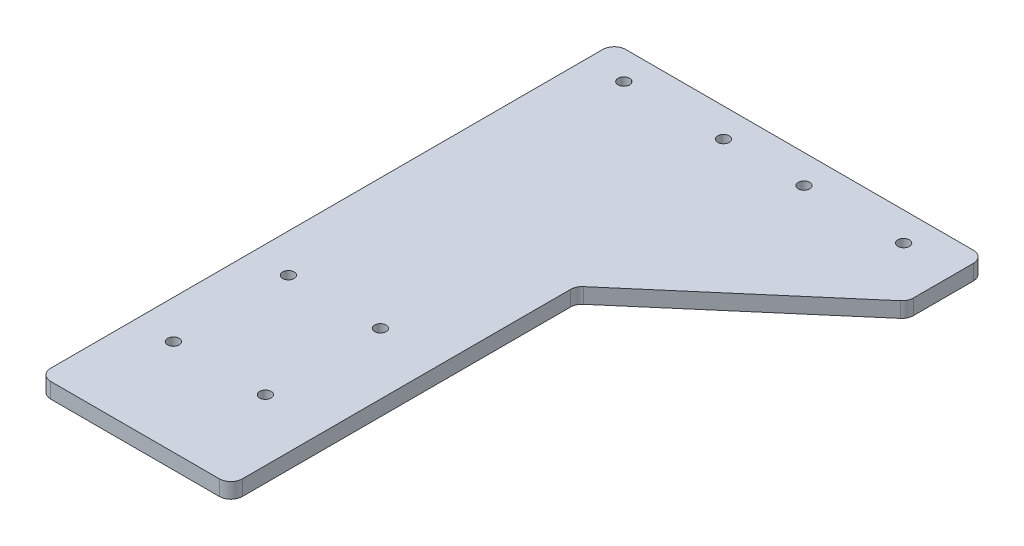
SolidWorks part; units mm, degrees
ref_plane "前视基准面" through (0, 0, 0) normal (0, 0, 1) x (1, 0, 0)
ref_plane "上视基准面" through (0, 0, 0) normal (0, 1, 0) x (1, 0, 0)
ref_plane "右视基准面" through (0, 0, 0) normal (1, 0, 0) x (0, 0, -1)
sketch "草图1" plane through (0, 0, 0) normal (0, 1, 0) x (1, 0, 0)
  line L0 (100, 150) -> (75, 0)
  line L1 (0, 0) -> (75, 0)
  line L2 (0, 0) -> (0, 150)
  line L3 (0, 150) -> (100, 150)
  dimension "D1" = 100
  dimension "D2" = 150
  dimension "D3" = 25
extrude "凸台-拉伸1" add sketch "草图1" along normal blind 4
sketch "草图2" plane through (0, 4, 0) normal (0, 1, 0) x (1, 0, 0)
  line L0 (0, 0) -> (75, 0) construction
  line L1 (0, 150) -> (0, 0) construction
  circle A0 centre (10, 25) radius 1.5
  circle A1 centre (34, 55) radius 1.5
  circle A2 centre (34, 25) radius 1.5
  circle A3 centre (10, 55) radius 1.5
  circle A4 centre (35, 25) radius 1.5 [skipped]
  circle A5 centre (35, 55) radius 1.5 [skipped]
  dimension "D1" = 25
  dimension "D2" = 10
  dimension "D3" = 2
  dimension "D4" = 2
  dimension "D5" = 2
extrude "切除-拉伸1" cut sketch "草图2" against normal blind 4
sketch "草图3" plane through (0, 4, 0) normal (0, 1, 0) x (1, 0, 0)
  line L0 (100, 150) -> (0, 150) construction
  line L1 (0, 150) -> (0, 0) construction
  circle A0 centre (10, 142.5) radius 1.5
  circle A1 centre (36, 142.5) radius 1.5
  circle A2 centre (57, 142.5) radius 1.5
  circle A3 centre (83, 142.5) radius 1.5
  dimension "D1" = 7.5
  dimension "D4" = 26
  dimension "D5" = 21
  dimension "D3" = 26
  dimension "D2" = 10
extrude "切除-拉伸2" cut sketch "草图3" against normal blind 4
sketch "草图4" plane through (0, 4, 0) normal (0, 1, 0) x (1, 0, 0)
  line L0 (121.6305, 0) -> (50, 0)
  line L1 (0, 0) -> (75, 0) construction
  line L2 (50, 0) -> (50, 90)
  line L3 (50, 90) -> (150.5378, 90)
  line L4 (150.5378, 90) -> (121.6305, 0)
  line L5 (0, 150) -> (0, 0) construction
  dimension "D1" = 50
  dimension "D2" = 90
extrude "切除-拉伸3" cut sketch "草图4" against normal blind 10
sketch "草图5" plane through (0, 4, 0) normal (0, 1, 0) x (1, 0, 0)
  line L0 (150.2124, 125.3523) -> (66.7705, 64.5463)
  line L1 (66.7705, 64.5463) -> (50, 90)
  line L2 (50, 90) -> (96.6667, 130)
  line L3 (90, 90) -> (100, 150) construction
  line L4 (96.6667, 130) -> (150.2124, 125.3523)
  line L5 (100, 150) -> (0, 150) construction
  dimension "D1" = 20
extrude "切除-拉伸5" cut sketch "草图5" against normal blind 10
sketch "草图6" plane through (0, 4, 0) normal (0, 1, 0) x (1, 0, 0)
  line L0 (96.6667, 130) -> (140.5543, 130)
  line L2 (96.6667, 130) -> (96.6667, 160.8612)
  line L3 (96.6667, 160.8612) -> (107.5065, 160.8612)
  line L4 (107.5065, 160.8612) -> (140.5543, 130)
extrude "切除-拉伸6" cut sketch "草图6" against normal blind 10
fillet "圆角1" radius 3 6 edges at (50, 2, 0) (50, 2, -90) (96.6667, 2, -130) (96.6667, 2, -150) (0, 2, -150) (0, 2, 0)
